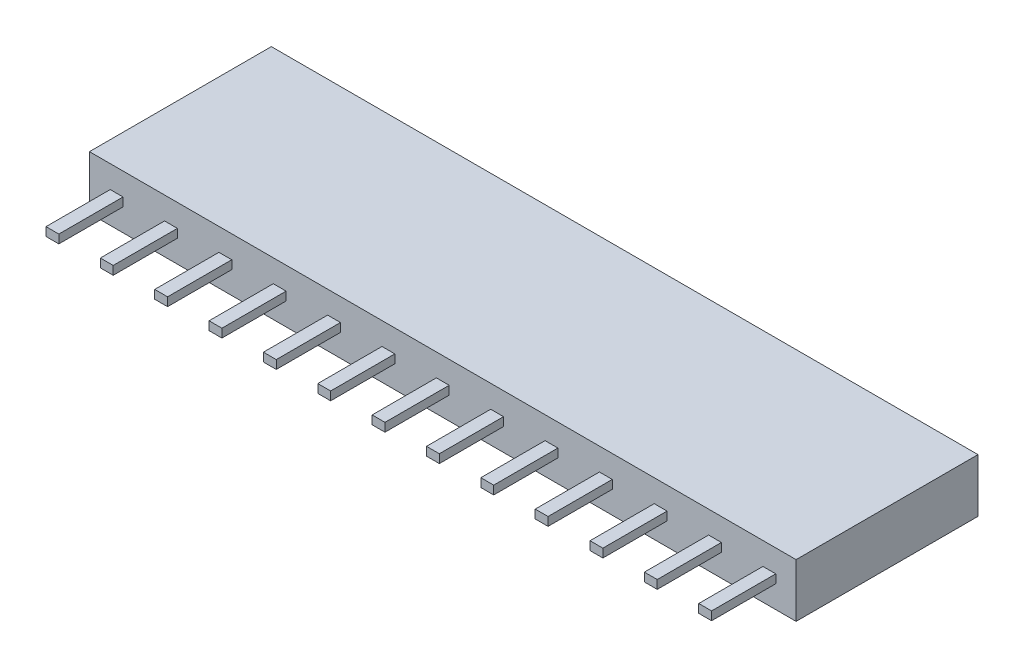
SolidWorks part; units mm, degrees
ref_plane "Front" through (0, 0, 0) normal (0, 0, 1) x (1, 0, 0)
ref_plane "Top" through (0, 0, 0) normal (0, 1, 0) x (1, 0, 0)
ref_plane "Right" through (0, 0, 0) normal (1, 0, 0) x (0, 0, -1)
sketch "Эскиз1" plane through (0, 0, 0) normal (0, 1, 0) x (1, 0, 0)
  line L1 (-16.51, 4.25) -> (16.51, 4.25)
  line L2 (-16.51, 4.25) -> (-16.51, -4.25)
  line L3 (-16.51, -4.25) -> (16.51, -4.25)
  line L4 (16.51, 4.25) -> (16.51, -4.25)
  line L5 (-16.51, 4.25) -> (16.51, -4.25) construction
  line L6 (-16.51, -4.25) -> (16.51, 4.25) construction
  point P0 (0, 0)
extrude "Бобышка-Вытянуть1" add sketch "Эскиз1" along normal blind 2.5
sketch "Эскиз2" plane through (0, 0, 4.25) normal (0, 0, 1) x (1, 0, 0)
  line L0 (-16.51, 1.25) -> (16.51, 1.25) construction
  line L1 (-16.51, 2.5) -> (-16.51, 0) construction
  line L2 (16.51, 2.5) -> (16.51, 0) construction
  line L3 (-7.92, 1.05) -> (-7.32, 1.05)
  line L4 (-10.46, 1.05) -> (-9.86, 1.05)
  line L5 (-10.46, 1.05) -> (-10.46, 1.45)
  line L6 (-10.46, 1.45) -> (-9.86, 1.45)
  line L7 (-9.86, 1.05) -> (-9.86, 1.45)
  line L8 (-10.46, 1.05) -> (-9.86, 1.45) construction
  line L9 (-10.46, 1.45) -> (-9.86, 1.05) construction
  line L10 (-7.92, 1.05) -> (-7.32, 1.45) construction
  line L11 (-7.92, 1.05) -> (-7.92, 1.45)
  line L12 (-7.92, 1.45) -> (-7.32, 1.45)
  line L13 (-7.92, 1.45) -> (-7.32, 1.05) construction
  line L14 (-7.32, 1.05) -> (-7.32, 1.45)
  line L15 (-5.38, 1.05) -> (-4.78, 1.05)
  line L16 (-5.38, 1.05) -> (-4.78, 1.45) construction
  line L17 (-5.38, 1.05) -> (-5.38, 1.45)
  line L18 (-5.38, 1.45) -> (-4.78, 1.45)
  line L19 (-5.38, 1.45) -> (-4.78, 1.05) construction
  line L20 (-4.78, 1.05) -> (-4.78, 1.45)
  line L21 (-2.84, 1.05) -> (-2.24, 1.05)
  line L22 (-2.84, 1.05) -> (-2.24, 1.45) construction
  line L23 (-2.84, 1.05) -> (-2.84, 1.45)
  line L24 (-2.84, 1.45) -> (-2.24, 1.45)
  line L25 (-2.84, 1.45) -> (-2.24, 1.05) construction
  line L26 (-2.24, 1.05) -> (-2.24, 1.45)
  line L27 (-0.3, 1.05) -> (0.3, 1.05)
  line L28 (-0.3, 1.05) -> (0.3, 1.45) construction
  line L29 (-0.3, 1.05) -> (-0.3, 1.45)
  line L30 (-0.3, 1.45) -> (0.3, 1.45)
  line L31 (-0.3, 1.45) -> (0.3, 1.05) construction
  line L32 (0.3, 1.05) -> (0.3, 1.45)
  line L33 (2.24, 1.05) -> (2.84, 1.05)
  line L34 (2.24, 1.05) -> (2.84, 1.45) construction
  line L35 (2.24, 1.05) -> (2.24, 1.45)
  line L36 (2.24, 1.45) -> (2.84, 1.45)
  line L37 (2.24, 1.45) -> (2.84, 1.05) construction
  line L38 (2.84, 1.05) -> (2.84, 1.45)
  line L39 (4.78, 1.05) -> (5.38, 1.05)
  line L40 (4.78, 1.05) -> (5.38, 1.45) construction
  line L41 (4.78, 1.05) -> (4.78, 1.45)
  line L42 (4.78, 1.45) -> (5.38, 1.45)
  line L43 (4.78, 1.45) -> (5.38, 1.05) construction
  line L44 (5.38, 1.05) -> (5.38, 1.45)
  line L45 (7.32, 1.05) -> (7.92, 1.05)
  line L46 (7.32, 1.05) -> (7.92, 1.45) construction
  line L47 (7.32, 1.05) -> (7.32, 1.45)
  line L48 (7.32, 1.45) -> (7.92, 1.45)
  line L49 (7.32, 1.45) -> (7.92, 1.05) construction
  line L50 (7.92, 1.05) -> (7.92, 1.45)
  line L51 (9.881, 1.45) -> (10.481, 1.05) construction
  line L52 (9.881, 1.45) -> (10.481, 1.45)
  line L53 (10.481, 1.05) -> (10.481, 1.45)
  line L54 (9.881, 1.05) -> (9.881, 1.45)
  line L55 (9.881, 1.05) -> (10.481, 1.45) construction
  line L56 (9.881, 1.05) -> (10.481, 1.05)
  line L57 (12.421, 1.45) -> (13.021, 1.45)
  line L58 (13.021, 1.05) -> (13.021, 1.45)
  line L59 (12.421, 1.05) -> (12.421, 1.45)
  line L60 (12.421, 1.05) -> (13.021, 1.05)
  line L61 (12.421, 1.45) -> (13.021, 1.05) construction
  line L62 (12.421, 1.05) -> (13.021, 1.45) construction
  line L63 (14.961, 1.45) -> (15.561, 1.45)
  line L64 (15.561, 1.05) -> (15.561, 1.45)
  line L65 (14.961, 1.05) -> (14.961, 1.45)
  line L66 (14.961, 1.05) -> (15.561, 1.05)
  line L67 (14.961, 1.45) -> (15.561, 1.05) construction
  line L68 (14.961, 1.05) -> (15.561, 1.45) construction
  line L69 (-13, 1.05) -> (-12.4, 1.05)
  line L70 (-13, 1.05) -> (-13, 1.45)
  line L71 (-13, 1.45) -> (-12.4, 1.45)
  line L72 (-12.4, 1.05) -> (-12.4, 1.45)
  line L73 (-13, 1.05) -> (-12.4, 1.45) construction
  line L74 (-13, 1.45) -> (-12.4, 1.05) construction
  line L75 (-15.54, 1.05) -> (-14.94, 1.05)
  line L76 (-15.54, 1.05) -> (-15.54, 1.45)
  line L77 (-15.54, 1.45) -> (-14.94, 1.45)
  line L78 (-14.94, 1.05) -> (-14.94, 1.45)
  line L79 (-15.54, 1.05) -> (-14.94, 1.45) construction
  line L80 (-15.54, 1.45) -> (-14.94, 1.05) construction
  dimension "D1" = 8
  dimension "D2" = 3
  dimension "D3" = 3
extrude "Бобышка-Вытянуть2" add sketch "Эскиз2" along normal blind 3
sketch "Эскиз3" plane through (0, 0, 7.25) normal (0, 0, 1) x (1, 0, 0)
  point P0 (-15.24, 1.25)
  point P2 (-12.7, 1.25)
  point P3 (-10.16, 1.25)
  point P4 (-7.62, 1.25)
  point P5 (-5.08, 1.25)
  point P6 (-2.54, 1.25)
  point P7 (0, 1.25)
  point P8 (2.54, 1.25)
  point P9 (5.08, 1.25)
  point P10 (7.62, 1.25)
  point P11 (10.16, 1.25)
  point P12 (12.7, 1.25)
  point P13 (15.24, 1.25)
  dimension "D1" = 13
